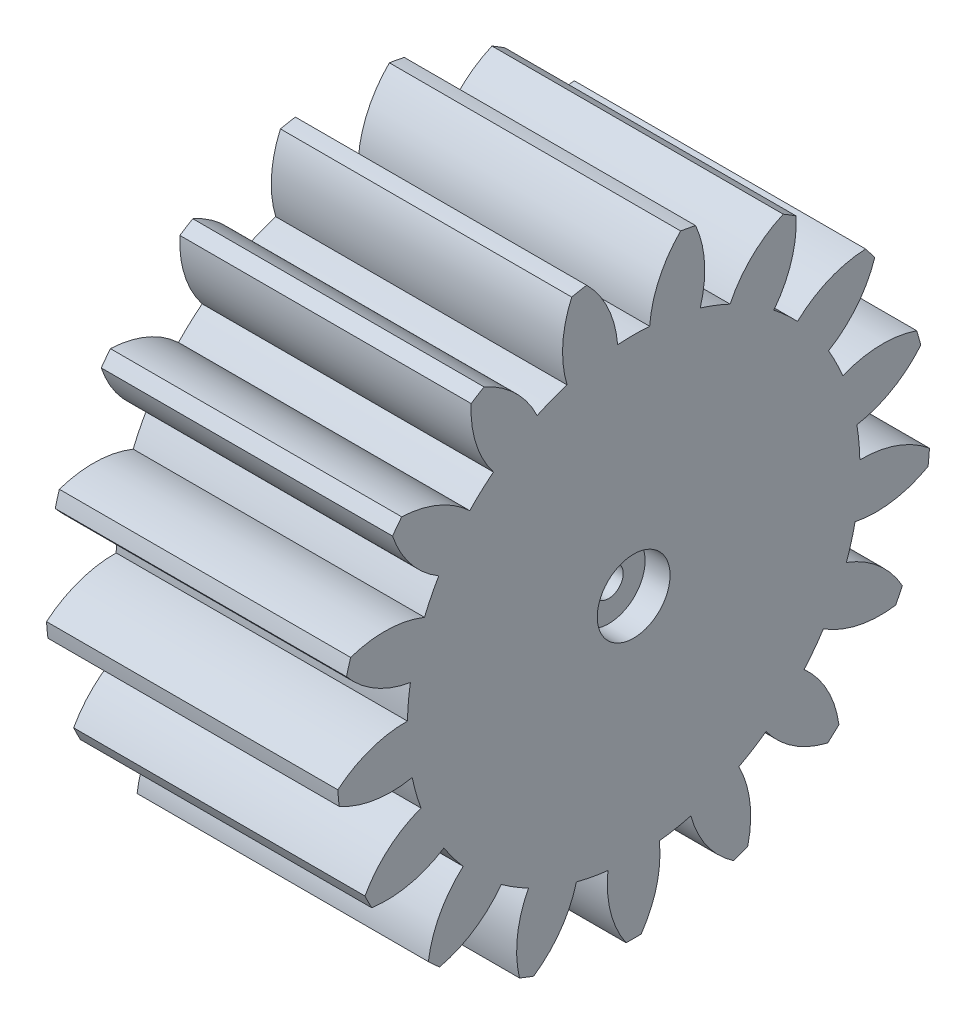
SolidWorks part; units mm, degrees
ref_plane "Plane1" through (0, 0, 0) normal (0, 0, 1) x (1, 0, 0)
ref_plane "Plane2" through (0, 0, 0) normal (0, 1, 0) x (1, 0, 0)
ref_plane "Plane3" through (0, 0, 0) normal (1, 0, 0) x (0, 0, -1)
other "Configuration Table"
sketch "HoldingSke" plane through (0, 0, 0) normal (0, 1, 0) x (1, 0, 0)
  line L0 (0, 0) -> (0.3188, -0.0975)
  line L1 (-15, 0) -> (100, 0) construction
  line L2 (0, 0) -> (-2.1039, 2.3779)
  line L3 (0, 0) -> (-11.863, 4.5341)
  line L4 (0, 0) -> (8.2586, 2.5249)
  line L5 (0, 0) -> (-46.8476, -17.4728)
  line L6 (0, 0) -> (-19.0661, -12.864)
  line L7 (-2.1039, 2.3779) -> (8.6586, 51.2059)
  line L8 (-76.2, 54.61) -> (-76.1, 54.61)
  line L9 (-71.009, 38.7566) -> (-53.1078, 45.2721)
  line L10 (-76.2, 71.12) -> (104.1128, 71.12)
  line L11 (0, 0) -> (-23, 0)
  line L12 (-76.2, 101.6) -> (-76.093, 101.6)
  line L13 (24.9733, 27.94) -> (52.9518, 28.4284)
  line L14 (24.9733, 27.94) -> (24.9743, 27.94)
  line L15 (24.9733, 27.94) -> (100.4006, 29.5858)
  line L16 (-63.627, -3) -> (-12.827, -3)
  circle A0 centre (0, 0) radius 0.4
  circle A1 centre (0, 0) radius 21.749
  circle A2 centre (0, 0) radius 37.5
  circle A3 centre (0, 0) radius 0.4
  dimension "MHD" = 43.498
  dimension "Hub_dia" = 75
  dimension "Bore" = 0.8
  dimension "MBD" = 0.8
  dimension "Num_teeth" = 17
  dimension "Pitch" = 0.3333
  dimension "Overall_len" = 50
  dimension "Show_teeth" = 17
  dimension "Thickness" = 23
  dimension "OAL" = 50.0001
  dimension "T_dim" = 0.1
  dimension "Ap" = 20
  dimension "H" = 19.05
  dimension "Pitch_radius" = 180.3128
  dimension "Width" = 23
  dimension "Backlash" = 0.107
  dimension "Addendum_fac" = 1
  dimension "Dedendum_fac" = 1.25
  dimension "Clearance_fac" = 0.25
  dimension "Dedendum_add" = 0.001
  dimension "Module" = 3
sketch "BasProSke" plane through (0, 0, 0) normal (0, 1, 0) x (1, 0, 0)
  line L0 (-10, 0) -> (60, 0) construction
  line L1 (0, 0) -> (0, 28.5)
  line L2 (0, 0) -> (28, 0)
  line L3 (28, 0) -> (28, 28.5)
  line L4 (28, 28.5) -> (0, 28.5)
  dimension "Thickness" = 28
  dimension "Diameter" = 57
revolve "Base-Revolve" add sketch "BasProSke" angle 360 about L0
sketch "TooCutSke" plane through (0, 0, 0) normal (1, 0, 0) x (0, 0, -1)
  line L1 (0, 0) -> (0, 107) construction
  line L2 (0, 0) -> (-2.54, 25.3732) construction
  line L3 (0, 0) -> (-9.3374, 49.9505) construction
  line L4 (-2.54, 25.3732) -> (-4.6687, 24.9753) construction
  arc A0 (1.5403, 21.6944) -> (-1.5403, 21.6944) centre (0, 0) ccw
  arc A1 (4.5406, 28.1617) -> (-4.5406, 28.1617) centre (0, 0) ccw
  circle A2 centre (0, 0) radius 25.5 construction
  circle A3 centre (0, 0) radius 23.9622 construction
  arc A4 (-1.5403, 21.6944) -> (-4.5406, 28.1617) centre (-11.7098, 20.9061) ccw
  arc A5 (4.5406, 28.1617) -> (1.5403, 21.6944) centre (11.7098, 20.9061) ccw
  dimension "Root_dia" = 43.498
  dimension "Overcut_dia" = 57.0508
  dimension "Pitch_dia" = 51
  dimension "Base_dia" = 47.9243
  dimension "Flank_rad" = 10.2
  dimension "Half_ang" = 10.588
  dimension "Half_CT" = 2.1656
extrude "ToothCut" cut sketch "TooCutSke" along normal through all
fillet "Breaks" [suppressed] radius 0.06
fillet "RootFillets" [suppressed] radius 0.751
pattern_circular "TeethCuts" count 17 every 21.176 about axis through (-10, 0, 0) along (1, 0, 0) of "ToothCut", "RootFillets", "Breaks"
sketch "HubNeaOneSke" plane through (0, 0, 0) normal (-1, 0, 0) x (0, 0, 1)
  circle A0 centre (0, 0) radius 21.749
  dimension "Diameter" = 43.498
extrude "HubNearOne" [suppressed] add sketch "HubNeaOneSke" along normal blind 22.0001
sketch "HubNeaBotSke" plane through (0, 0, 0) normal (-1, 0, 0) x (0, 0, 1)
  circle A0 centre (0, 0) radius 21.749
  dimension "Diameter" = 43.498
extrude "HubNearBoth" [suppressed] add sketch "HubNeaBotSke" along normal blind 11
ref_plane "FarPln" through (28, 0, 0) normal (1, 0, 0) x (0, 0, -1)
sketch "HubFarSke" plane through (28, 0, 0) normal (1, 0, 0) x (0, 0, -1)
  circle A0 centre (0, 0) radius 21.749
  dimension "Diameter" = 43.498
extrude "HubFar" [suppressed] add sketch "HubFarSke" along normal blind 11
sketch "BorSke" plane through (0, 0, 0) normal (1, 0, 0) x (0, 0, -1)
  circle A0 centre (0, 0) radius 0.4
  dimension "Diameter" = 0.8
extrude "Bore" cut sketch "BorSke" along normal mid plane 100.0001
sketch "KeySke" plane through (0, 0, 0) normal (1, 0, 0) x (0, 0, -1)
  line L0 (-0.05, 0) -> (-0.05, 0.5)
  line L1 (-0.05, 0.5) -> (0.05, 0.5)
  line L2 (0.05, 0.5) -> (0.05, 0)
  line L3 (0, 0) -> (0, 34) construction
  line L4 (-0.05, 0) -> (0.05, 0)
  dimension "Offset" = 0.5
  dimension "Width" = 0.1
extrude "Keyway" [suppressed] cut sketch "KeySke" along normal mid plane 100.0001
pattern_circular "Keyway2" [suppressed] count 2 every 90 about axis through (-10, 0, 0) along (1, 0, 0)
sketch "Sketch1" plane through (0, 0, 0) normal (-1, 0, 0) x (0, 0, 1)
  line L1 (0, -7.5) -> (6.4952, -3.75)
  line L2 (6.4952, -3.75) -> (6.4952, 3.75)
  line L3 (6.4952, 3.75) -> (0, 7.5)
  line L4 (0, 7.5) -> (-6.4952, 3.75)
  line L5 (-6.4952, 3.75) -> (-6.4952, -3.75)
  line L6 (-6.4952, -3.75) -> (0, -7.5)
  circle A0 centre (0, 0) radius 6.4952 construction
  dimension "D1" = 15
extrude "Cut-Extrude1" cut sketch "Sketch1" against normal offset from surface (21 mm away) 7 up to face at (28, 0, 0.4)
sketch "Sketch2" plane through (28, 0, 0) normal (1, 0, 0) x (0, 0, -1)
  point P0 (0, 0)
hole_wizard "CBORE for M3 Pan Head Screw1" positions "Sketch2" profile "Sketch3" counterbore size "M3" standard "ISO" end condition through all
sketch "Sketch3" plane through (28, 0, 0) normal (0, 1, 0) x (0, 0, -1)
  line L0 (0, 0) -> (0, 28)
  line L1 (0, 28) -> (1.4, 28)
  line L3 (1.4, 28) -> (1.4, 2.4)
  line L4 (1.4, 2.4) -> (3.5, 2.4)
  line L5 (3.5, 2.4) -> (3.5, 0)
  line L7 (3.5, 0) -> (0, 0)
  line L11 (0, -6.35) -> (0, 107.95) construction
  dimension "Thru Hole Dia." = 2.8
  dimension "Thru Hole Depth" = 28
  dimension "C'Bore Dia." = 7
  dimension "C'Bore Depth" = 2.4
fillet "Fillet1" radius 0.5 12 edges at (0, 0, -6.4952) (0, -5.625, -3.2476) (0, 5.625, -3.2476) (0, -5.625, 3.2476) (0, 5.625, 3.2476) (0, 0, 6.4952) (10.5, -3.75, -6.4952) (10.5, 3.75, -6.4952) (10.5, 7.5, 0) (10.5, 3.75, 6.4952) (10.5, -3.75, 6.4952) (10.5, -7.5, 0)
equation "' \"Module@HoldingSke\" = 6.35"
equation "' \"Num_teeth@HoldingSke\" = 12"
equation "' \"Ap@HoldingSke\" =  20"
equation "' \"Ap@HoldingSke\" = 20"
equation "' \"Width@HoldingSke\" = 0.5 * 25.4"
equation "' \"Hub_dia@HoldingSke\"= 1 * 25.4"
equation "' \"Hub_dia@HoldingSke\" = 1 * 25.4"
equation "' \"Overall_len@HoldingSke\" = 1.0 * 25.4"
equation "' \"Bore@HoldingSke\" = 0.75 * 25.4"
equation "' \"T_dim@HoldingSke\" = 0.1 * 25.4"
equation "' \"Width@KeySke\" = 0.25 * 25.4"
equation "' \"Show_teeth@HoldingSke\" = 13"
equation "' \"Backlash@HoldingSke\" = 0.009 * 25.4"
equation "' \"Addendum_fac@HoldingSke\" = 1.0"
equation "' \"Dedendum_fac@HoldingSke\" = 1.25"
equation "' \"Dedendum_add@HoldingSke\" = 0.00005 * 25.4"
equation "' \"Clearance_fac@HoldingSke\" = 0.25"
equation "\"Pitch@HoldingSke\" = 1 / \"Module@HoldingSke\""
equation "\"Overcut_dia@TooCutSke\" = (\"Num_teeth@HoldingSke\" + 2 * \"Addendum_fac@HoldingSke\") / \"Pitch@HoldingSke\" + 0.002 * 25.4"
equation "\"Pitch_dia@TooCutSke\" = \"Num_teeth@HoldingSke\" / \"Pitch@HoldingSke\""
equation "\"Base_dia@TooCutSke\" = \"Num_teeth@HoldingSke\" / \"Pitch@HoldingSke\" * cos((\"Ap@HoldingSke\"  * 3.14159265 / 180))"
equation "\"Root_dia@TooCutSke\" = (\"Num_teeth@HoldingSke\" + 2) / \"Pitch@HoldingSke\" - 2 * (\"Addendum_fac@HoldingSke\" + \"Dedendum_fac@HoldingSke\") / \"Pitch@HoldingSke\" - \"Dedendum_add@HoldingSke\" * 2"
equation "\"Half_ang@TooCutSke\" = 180 / \"Num_teeth@HoldingSke\""
equation "\"Half_CT@TooCutSke\" = \"Num_teeth@HoldingSke\" / \"Pitch@HoldingSke\" * sin((3.14159265 / 2 / \"Num_teeth@HoldingSke\")) / 2 - 7 * \"Backlash@HoldingSke\" / 4"
equation "\"Flank_rad@TooCutSke\" = \"Num_teeth@HoldingSke\" / \"Pitch@HoldingSke\" / 5"
equation "\"Radius@RootFillets\" = \"Clearance_fac@HoldingSke\" / \"Pitch@HoldingSke\" + \"Dedendum_add@HoldingSke\""
equation "\"Break_rad@Breaks\" = 0.02 / \"Pitch@HoldingSke\""
equation "\"Thickness@HoldingSke\" = \"Width@HoldingSke\""
equation "\"OAL@HoldingSke\" = \"Thickness@HoldingSke\""
equation "\"MHD@HoldingSke\" = (\"Num_teeth@HoldingSke\" + 2) / \"Pitch@HoldingSke\" - 2 * (\"Addendum_fac@HoldingSke\" + \"Dedendum_fac@HoldingSke\")  / \"Pitch@HoldingSke\" - \"Dedendum_add@HoldingSke\" * 2"
equation "\"MBD@HoldingSke\" = (\"Num_teeth@HoldingSke\" + 2) / \"Pitch@HoldingSke\" - 2 * (\"Addendum_fac@HoldingSke\" + \"Dedendum_fac@HoldingSke\")  / \"Pitch@HoldingSke\" - \"Dedendum_add@HoldingSke\" * 2 - 0.002 * 25.4"
equation "\"MHD@HoldingSke\" = ((sgn( \"MHD@HoldingSke\" - \"Hub_dia@HoldingSke\" )-1)*( \"MHD@HoldingSke\" - \"Hub_dia@HoldingSke\" ))/-2+ \"Hub_dia@HoldingSke\""
equation "\"MBD@HoldingSke\" = ((sgn( \"MBD@HoldingSke\" - \"Bore@HoldingSke\" )-1)*( \"MBD@HoldingSke\" - \"Bore@HoldingSke\" ))/-2+ \"Bore@HoldingSke\""
equation "\"OAL@HoldingSke\" = ((sgn( \"OAL@HoldingSke\" - \"Overall_len@HoldingSke\" )+1)*( \"OAL@HoldingSke\" - \"Overall_len@HoldingSke\" ))/2 + \"Overall_len@HoldingSke\" + 0.000002 * 25.4"
equation "\"Num_teeth@TeethCuts\" = int( \"Show_teeth@HoldingSke\" ) + 1"
equation "\"Num_teeth@TeethCuts\" = ((sgn( \"Num_teeth@TeethCuts\" - \"Num_teeth@HoldingSke\" )-1)*( \"Num_teeth@TeethCuts\" - \"Num_teeth@HoldingSke\" ))/-2+ \"Num_teeth@HoldingSke\""
equation "\"Num_teeth@TeethCuts\" = ((sgn( \"Num_teeth@TeethCuts\" - 2.0)+1)*( \"Num_teeth@TeethCuts\" - 2.0))/2 +2.0"
equation "\"Angle@TeethCuts\" = 360.0 / \"Num_teeth@HoldingSke\""
equation "\"Diameter@BasProSke\" = (\"Num_teeth@HoldingSke\" + 2 * \"Addendum_fac@HoldingSke\") / \"Pitch@HoldingSke\""
equation "\"Thickness@BasProSke\"=28"
equation "' \"Fillet_rad@BasProSke\" =  \"Thickness@HoldingSke\" * 0.05"
equation "' \"Fillet_rad@BasProSke\" = \"Thickness@HoldingSke\" * 0.05"
equation "\"MHD@HoldingSke\" = ((sgn( \"MHD@HoldingSke\" - \"Root_dia@TooCutSke\" )-1)*( \"MHD@HoldingSke\" - \"Root_dia@TooCutSke\" ))/-2+ \"Root_dia@TooCutSke\""
equation "\"Diameter@HubNeaOneSke\" = \"MHD@HoldingSke\""
equation "\"Length@HubNearOne\" = \"OAL@HoldingSke\" - \"Thickness@BasProSke\""
equation "\"Diameter@HubNeaBotSke\" = \"MHD@HoldingSke\""
equation "\"Length@HubNearBoth\" = ( \"OAL@HoldingSke\" - \"Thickness@BasProSke\" ) / 2.0"
equation "\"Thickness@FarPln\" = \"Thickness@BasProSke\""
equation "\"Diameter@HubFarSke\" = \"MHD@HoldingSke\""
equation "\"Length@HubFar\" = ( \"OAL@HoldingSke\" - \"Thickness@BasProSke\" ) / 2.0"
equation "\"Diameter@BorSke\" = \"MBD@HoldingSke\""
equation "\"D1@Bore\" = \"OAL@HoldingSke\" * 2.0"
equation "\"D1@Keyway\" = \"OAL@HoldingSke\" * 2.0"
equation "\"Offset@KeySke\" = \"T_dim@HoldingSke\" + \"MBD@HoldingSke\" / 2.0"
